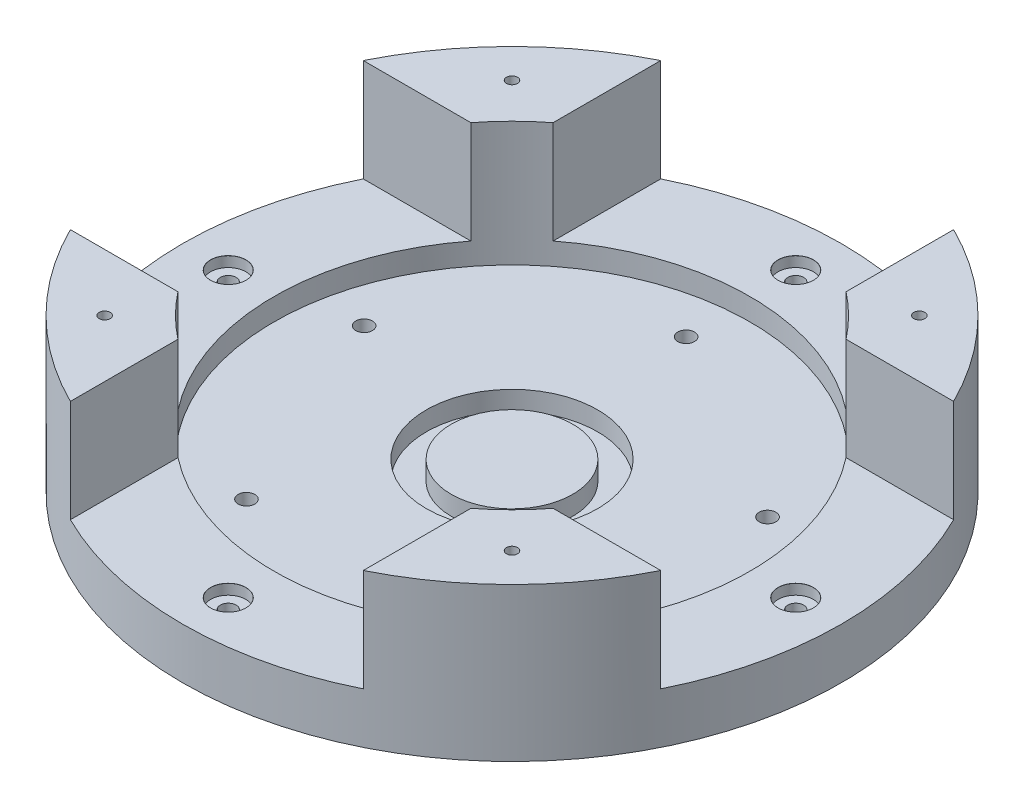
SolidWorks part; units mm, degrees
ref_plane "Front Plane" through (0, 0, 0) normal (0, 0, 1) x (1, 0, 0)
ref_plane "Top Plane" through (0, 0, 0) normal (0, 1, 0) x (1, 0, 0)
ref_plane "Right Plane" through (0, 0, 0) normal (1, 0, 0) x (0, 0, -1)
sketch "Sketch1" plane through (0, 0, 0) normal (0, 1, 0) x (1, 0, 0)
  line L1 (-150, 150) -> (150, 150)
  line L2 (-150, 150) -> (-150, -150)
  line L3 (-150, -150) -> (150, -150)
  line L4 (150, 150) -> (150, -150)
  line L5 (-150, 150) -> (150, -150) construction
  line L6 (-150, -150) -> (150, 150) construction
  point P0 (0, 0)
  dimension "D1" = 300
extrude "Boss-Extrude1" add sketch "Sketch1" along normal blind 10
sketch "Sketch2" plane through (0, 10, 0) normal (0, 1, 0) x (1, 0, 0)
  circle A0 centre (0, 0) radius 127
  dimension "D1" = 254
extrude "Boss-Extrude2" add sketch "Sketch2" along normal blind 53.594
sketch "Sketch4" plane through (0, 63.594, 0) normal (0, 1, 0) x (1, 0, 0)
  circle A2 centre (0, 0) radius 122
  circle A3 centre (0, 0) radius 122
  dimension "D1" = 5
extrude "Cut-Extrude1" cut sketch "Sketch4" against normal blind 3
hole_wizard "CBORE for M6 Hex Head Bolt1" positions "Sketch6" profile "Sketch7" counterbore size "M6" standard "ANSI Metric" end condition through all
sketch "Sketch6" plane through (0, 10, 0) normal (0, 1, 0) x (1, 0, 0)
  point P0 (-101.6, 101.6)
  point P2 (101.6, 101.6)
  point P4 (101.6, -101.6)
  point P6 (-101.6, -101.6)
  dimension "D1" = 203.2
  dimension "D2" = 203.2
  dimension "D3" = 101.6
  dimension "D4" = 101.6
sketch "Sketch7" plane through (-101.6, 10, -101.6) normal (1, 0, 0) x (0, 0, 1)
  line L0 (0, 0) -> (0, 10)
  line L1 (0, 10) -> (3.3, 10)
  line L3 (3.3, 10) -> (3.3, 4.38)
  line L4 (3.3, 4.38) -> (7.275, 4.38)
  line L5 (7.275, 4.38) -> (7.275, 0)
  line L7 (7.275, 0) -> (0, 0)
  line L11 (0, -6.35) -> (0, 107.95) construction
  dimension "Thru Hole Dia." = 6.6
  dimension "Thru Hole Depth" = 10
  dimension "C'Bore Dia." = 14.55
  dimension "C'Bore Depth" = 4.38
fillet "Fillet1" radius 10 4 edges at (150, 5, 150) (-150, 5, -150) (150, 5, -150) (-150, 5, 150)
fillet "Fillet2" radius 2 8 edges at (-147.0711, 10, 147.0711) (-150, 10, 0) (-147.0711, 10, -147.0711) (0, 10, -150) (147.0711, 10, -147.0711) (150, 10, 0) (147.0711, 10, 147.0711) (0, 10, 150)
sketch "Sketch8" plane through (0, 60.594, 0) normal (0, 1, 0) x (1, 0, 0)
  circle A1 centre (0, 0) radius 122
  circle A2 centre (0, 0) radius 122
  dimension "D1" = 0
extrude "Cut-Extrude2" cut sketch "Sketch8" against normal up to surface (50.594 mm away) up to face at (0, 10, 0)
sketch "Sketch10" plane through (0, 10, 0) normal (0, 1, 0) x (1, 0, 0)
  circle A0 centre (0, 0) radius 114.3
  circle A1 centre (0, 0) radius 82.55
  dimension "D1" = 228.6
  dimension "D2" = 165.1
extrude "Boss-Extrude3" add sketch "Sketch10" along normal blind 43.18
sketch "Sketch11" plane through (0, 53.18, 0) normal (0, 1, 0) x (1, 0, 0)
  line L0 (25.4, 25.4) -> (139.7, 25.4)
  line L1 (-139.7, -25.4) -> (-25.4, -25.4)
  line L2 (-139.7, -25.4) -> (-139.7, 25.4)
  line L3 (-139.7, 25.4) -> (-25.4, 25.4)
  line L4 (139.7, -25.4) -> (139.7, 25.4)
  line L5 (-139.7, -25.4) -> (139.7, 25.4) construction
  line L6 (-139.7, 25.4) -> (139.7, -25.4) construction
  line L7 (-25.4, -139.7) -> (25.4, -139.7)
  line L8 (-25.4, -139.7) -> (-25.4, -25.4)
  line L9 (-25.4, 139.7) -> (25.4, 139.7)
  line L10 (25.4, -139.7) -> (25.4, -25.4)
  line L11 (-25.4, -139.7) -> (25.4, 139.7) construction
  line L12 (-25.4, 139.7) -> (25.4, -139.7) construction
  line L13 (25.4, 25.4) -> (25.4, 139.7)
  line L14 (-25.4, 25.4) -> (-25.4, 139.7)
  line L15 (25.4, -25.4) -> (139.7, -25.4)
  point P0 (0, 0)
  point P6 (0, 0)
  dimension "D1" = 50.8
  dimension "D2" = 279.4
  dimension "D3" = 50.8
  dimension "D4" = 279.4
  dimension "D5" = 114.3
  dimension "D6" = 114.3
extrude "Cut-Extrude3" cut sketch "Sketch11" against normal blind 15.24 and the other way blind 25.4
sketch "Sketch12" plane through (0, 53.18, 0) normal (0, 1, 0) x (1, 0, 0)
  circle A0 centre (70.6501, 70.6501) radius 1.905
  circle A1 centre (-70.6501, 70.6501) radius 1.905
  circle A2 centre (-70.6501, -70.6501) radius 1.905
  circle A3 centre (70.6501, -70.6501) radius 1.905
  dimension "D1" = 3.81
  dimension "D2" = 141.3002
  dimension "D3" = 141.3002
  dimension "D4" = 70.6501
  dimension "D5" = 70.6501
  dimension "D6" = 70.6501
  dimension "D7" = 141.3002
  dimension "D8" = 70.6501
  dimension "D9" = 70.6501
extrude "Cut-Extrude4" cut sketch "Sketch12" against normal blind 5.08
hole_wizard "CBORE for M5 Hex Head Machine Screw1" positions "Sketch14" profile "Sketch15" counterbore size "M5" standard "ANSI Metric" end condition through all
sketch "Sketch14" plane through (0, 0, 0) normal (0, -1, 0) x (-1, 0, 0)
  circle A0 centre (0, 0) radius 67.31
  point P0 (-44.6999, -50.3245)
  point P3 (-61.6745, 26.961)
  point P6 (6.583, 66.9873)
  point P9 (65.743, 14.4394)
  point P12 (34.0484, -58.0633)
  dimension "D1" = 6.583
  dimension "D2" = 61.6745
sketch "Sketch15" plane through (44.6999, 0, 50.3245) normal (1, 0, 0) x (0, 0, -1)
  line L0 (0, 0) -> (0, 63.594)
  line L1 (0, 63.594) -> (2.9, 63.594)
  line L3 (2.9, 63.594) -> (2.9, 3.8)
  line L4 (2.9, 3.8) -> (5.855, 3.8)
  line L5 (5.855, 3.8) -> (5.855, 0)
  line L7 (5.855, 0) -> (0, 0)
  line L11 (0, -6.35) -> (0, 107.95) construction
  dimension "Thru Hole Dia." = 5.8
  dimension "Thru Hole Depth" = 63.594
  dimension "C'Bore Dia." = 11.71
  dimension "C'Bore Depth" = 3.8
sketch "Sketch16" plane through (0, 10, 0) normal (0, 1, 0) x (1, 0, 0)
  circle A0 centre (0, 0) radius 29.718
  circle A2 centre (0, 0) radius 21.082
  dimension "D1" = 42.164
  dimension "D2" = 59.436
extrude "Cut-Extrude5" cut sketch "Sketch16" against normal blind 6.604
sketch "Sketch17" plane through (0, 10, 0) normal (0, 1, 0) x (1, 0, 0)
  circle A0 centre (0, 0) radius 127
  circle A1 centre (0, 0) radius 127 construction
  circle A2 centre (0, 0) radius 254
  dimension "D1" = 508
extrude "Cut-Extrude6" cut sketch "Sketch17" against normal through all both and the other way through all
sketch "Sketch18" plane through (0, 53.18, 0) normal (0, 1, 0) x (1, 0, 0)
  line L0 (0, 82.55) -> (0, 127) construction
  line L1 (50.8, 65.0681) -> (50.8, 102.3907)
  line L2 (-50.8, 65.0681) -> (-50.8, 102.3907)
  line L4 (-50.8, -102.3907) -> (-50.8, -65.0681)
  line L6 (50.8, -102.3907) -> (50.8, -65.0681)
  line L9 (-102.3907, -50.8) -> (-65.0681, -50.8)
  line L11 (-102.3907, 50.8) -> (-65.0681, 50.8)
  line L15 (65.0681, 50.8) -> (102.3907, 50.8)
  line L17 (65.0681, -50.8) -> (102.3907, -50.8)
  circle A0 centre (0, 0) radius 114.3
  arc A1 (111.442, 25.4) -> (25.4, 111.442) centre (0, 0) ccw construction
  arc A2 (65.0681, 50.8) -> (65.0681, -50.8) centre (0, 0) ccw
  arc A3 (25.4, 78.5452) -> (-25.4, 78.5452) centre (0, 0) ccw construction
  arc A4 (25.4, 124.4341) -> (-25.4, 124.4341) centre (0, 0) ccw construction
  arc A5 (65.0681, 50.8) -> (65.0681, -50.8) centre (0, 0) cw
  arc M14 (-78.5452, 25.4) -> (-25.4, 78.5452) centre (0, 0) cw
  line M15 (-25.4, 78.5452) -> (-25.4, 111.442)
  arc M16 (-25.4, 111.442) -> (-111.442, 25.4) centre (0, 0) ccw
  line M17 (-111.442, 25.4) -> (-78.5452, 25.4)
  dimension "D1" = 101.6
  dimension "D2" = 101.6
  dimension "D3" = 50.8
  dimension "D4" = 50.8
  dimension "D5" = 50.8
  dimension "D6" = 50.8
extrude "Cut-Extrude7" cut sketch "Sketch18" against normal up to surface (15.24 mm away) contours A2 A0 L9 M17 | L11 M16 M17 M14 | L2 M14 M15 M16 | A2 L0 A0 M15 | L0 A2 L1 A0 | L15 A5 L17 A0 | A2 L4 A0 L6 up to face at (0, 37.94, 96.7093)
sketch "Sketch19" plane through (0, 37.94, 0) normal (0, 1, 0) x (1, 0, 0)
  line L0 (50.8, -102.3907) -> (50.8, -65.0681) construction
  line L1 (-50.8, -65.0681) -> (-50.8, -102.3907) construction
  line L2 (102.3907, 50.8) -> (65.0681, 50.8) construction
  line L3 (65.0681, -50.8) -> (102.3907, -50.8) construction
  line L4 (-50.8, 102.3907) -> (-50.8, 65.0681) construction
  line L5 (50.8, 65.0681) -> (50.8, 102.3907) construction
  line L6 (-102.3907, -50.8) -> (-65.0681, -50.8) construction
  line L7 (-65.0681, 50.8) -> (-102.3907, 50.8) construction
  line L8 (50.8, -102.3907) -> (50.8, -65.0681)
  line L9 (-50.8, -65.0681) -> (-50.8, -102.3907)
  line L10 (102.3907, 50.8) -> (65.0681, 50.8)
  line L11 (65.0681, -50.8) -> (102.3907, -50.8)
  line L12 (-50.8, 102.3907) -> (-50.8, 65.0681)
  line L13 (50.8, 65.0681) -> (50.8, 102.3907)
  line L14 (-102.3907, -50.8) -> (-65.0681, -50.8)
  line L15 (-65.0681, 50.8) -> (-102.3907, 50.8)
  arc A0 (-50.8, -102.3907) -> (50.8, -102.3907) centre (0, 0) ccw construction
  arc A1 (-50.8, -65.0681) -> (50.8, -65.0681) centre (0, 0) ccw construction
  arc A2 (102.3907, -50.8) -> (102.3907, 50.8) centre (0, 0) ccw construction
  arc A3 (65.0681, -50.8) -> (65.0681, 50.8) centre (0, 0) ccw construction
  arc A4 (50.8, 102.3907) -> (-50.8, 102.3907) centre (0, 0) ccw construction
  arc A5 (50.8, 65.0681) -> (-50.8, 65.0681) centre (0, 0) ccw construction
  arc A6 (-102.3907, 50.8) -> (-102.3907, -50.8) centre (0, 0) ccw construction
  arc A7 (-65.0681, 50.8) -> (-65.0681, -50.8) centre (0, 0) ccw construction
  arc A8 (-50.8, -102.3907) -> (50.8, -102.3907) centre (0, 0) ccw
  arc A9 (-50.8, -65.0681) -> (50.8, -65.0681) centre (0, 0) ccw
  arc A10 (102.3907, -50.8) -> (102.3907, 50.8) centre (0, 0) ccw
  arc A11 (65.0681, -50.8) -> (65.0681, 50.8) centre (0, 0) ccw
  arc A12 (50.8, 102.3907) -> (-50.8, 102.3907) centre (0, 0) ccw
  arc A13 (50.8, 65.0681) -> (-50.8, 65.0681) centre (0, 0) ccw
  arc A14 (-102.3907, 50.8) -> (-102.3907, -50.8) centre (0, 0) ccw
  arc A15 (-65.0681, 50.8) -> (-65.0681, -50.8) centre (0, 0) ccw
extrude "Cut-Extrude8" cut sketch "Sketch19" against normal blind 20.32
hole_wizard "CBORE for M5 Hex Head Bolt1" positions "Sketch20" profile "Sketch21" counterbore size "M5" standard "ANSI Metric" end condition through all
sketch "Sketch20" plane through (0, 17.62, 0) normal (0, 1, 0) x (1, 0, 0)
  point P0 (-98.425, 0)
  point P2 (98.425, 0)
  point P4 (0, 98.425)
  point P6 (0, -98.425)
  dimension "D2" = 98.425
  dimension "D1" = 98.425
  dimension "D3" = 98.425
  dimension "D4" = 98.425
sketch "Sketch21" plane through (-98.425, 17.62, 0) normal (1, 0, 0) x (0, 0, 1)
  line L0 (0, 0) -> (0, 17.62)
  line L1 (0, 17.62) -> (2.75, 17.62)
  line L3 (2.75, 17.62) -> (2.75, 3.58)
  line L4 (6.12, 3.58) -> (2.75, 3.58)
  line L5 (6.12, 3.58) -> (6.12, 0.021)
  line L6 (6.12, 0.021) -> (6.145, 0)
  line L7 (6.145, 0) -> (0, 0)
  line L8 (-6.12, 0.021) -> (-6.145, 0) construction
  line L11 (0, -6.35) -> (0, 107.95) construction
  dimension "Thru Hole Dia." = 5.5
  dimension "Thru Hole Depth" = 17.62
  dimension "C'Bore Dia." = 12.24
  dimension "C'Bore Depth" = 3.58
  dimension "Near C'Sink Dia." = 12.29
  dimension "Near C'Sink Angle" = 100
sketch "Sketch22" plane through (0, 10, 0) normal (0, 1, 0) x (1, 0, 0)
  circle A0 centre (0, 0) radius 114.3
  arc A1 (50.8, 102.3907) -> (-50.8, 102.3907) centre (0, 0) ccw construction
  circle A2 centre (0, 0) radius 139.7
  dimension "D1" = 279.4
extrude "Cut-Extrude9" cut sketch "Sketch22" against normal through all both and the other way through all
